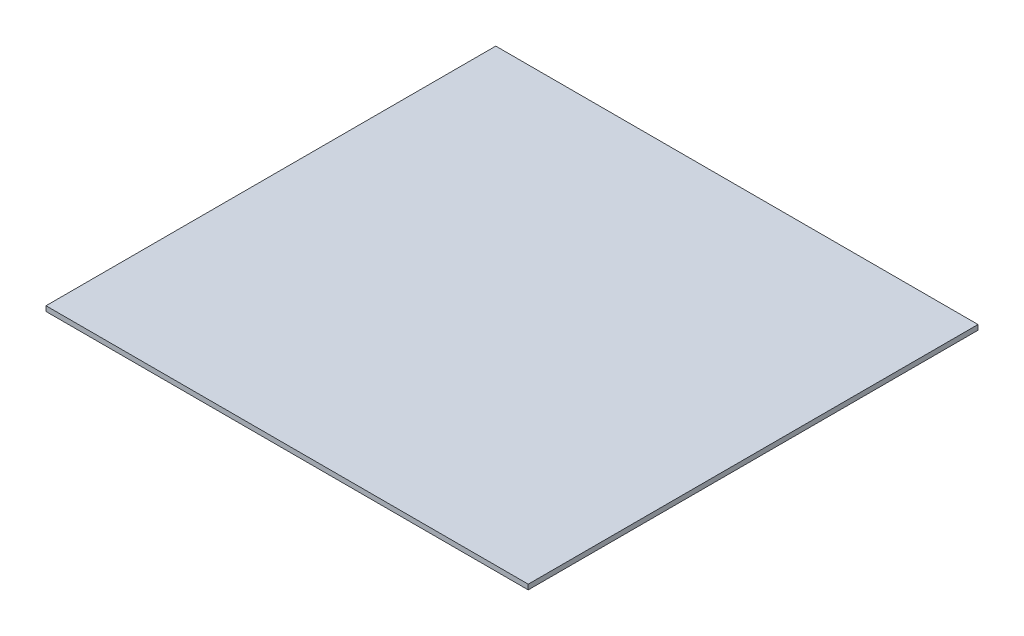
SolidWorks part; units mm, degrees
ref_plane "Front Plane" through (0, 0, 0) normal (0, 0, 1) x (1, 0, 0)
ref_plane "Top Plane" through (0, 0, 0) normal (0, 1, 0) x (1, 0, 0)
ref_plane "Right Plane" through (0, 0, 0) normal (1, 0, 0) x (0, 0, -1)
sketch "Sketch1" plane through (0, 0, 0) normal (0, 1, 0) x (1, 0, 0)
  line L0 (0, 10.8424) -> (0, -12.7011) construction
  line L1 (-4.825, 4.5) -> (4.825, 4.5)
  line L2 (-4.825, 4.5) -> (-4.825, -4.5)
  line L3 (-4.825, -4.5) -> (4.825, -4.5)
  line L4 (4.825, 4.5) -> (4.825, -4.5)
  line L5 (-8.5707, 0) -> (13.9402, 0) construction
  dimension "D1" = 9
  dimension "D2" = 9.65
extrude "Boss-Extrude1" add sketch "Sketch1" along normal blind 0.1
